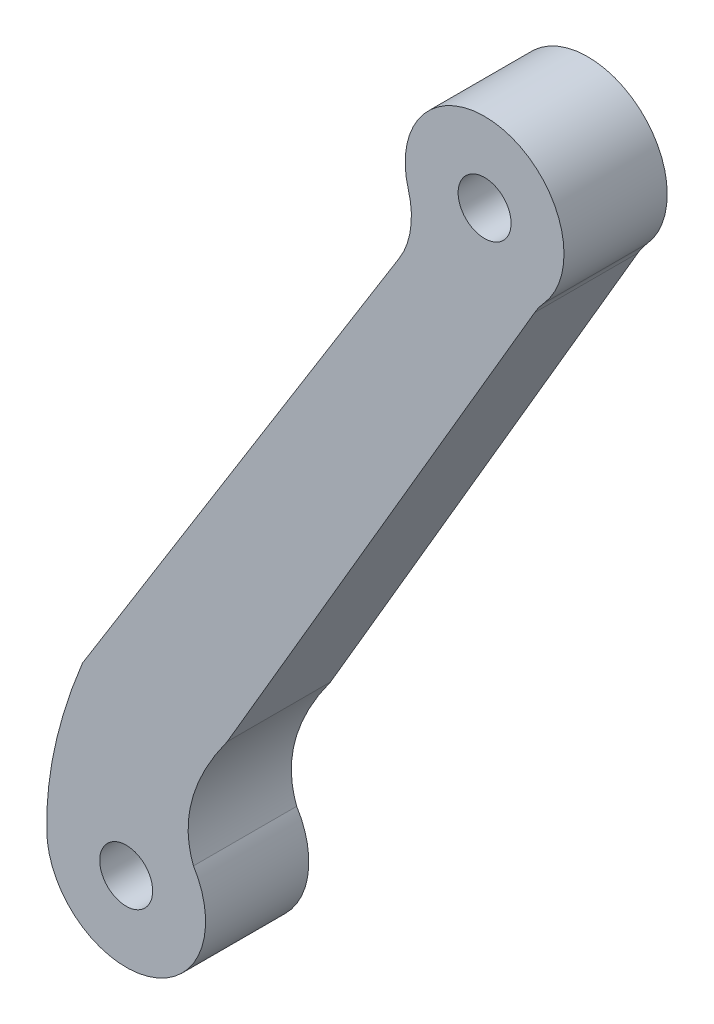
SolidWorks part; units mm, degrees
ref_plane "Спереди" through (0, 0, 0) normal (0, 0, 1) x (1, 0, 0)
ref_plane "Сверху" through (0, 0, 0) normal (0, 1, 0) x (1, 0, 0)
ref_plane "Справа" through (0, 0, 0) normal (1, 0, 0) x (0, 0, -1)
sketch "Sketch5" plane through (0, 0, 0) normal (0, 0, 1) x (1, 0, 0)
  line L0 (1.7523, 0.4742) -> (37.3029, 86.8114) construction
  line L1 (-1.0106, -0.6044) -> (29.6618, 87.5839) construction
  line L2 (0, 0) -> (17.8901, 43.1295)
  line L3 (0, 0) -> (114.3643, 0) construction
  line L4 (23.8823, 39.6684) -> (24.5035, 51.2503)
  line B0 (17.4507, 115.16) -> (29.9551, 112.6983)
  spline B1 degree 3 poles (29.9551, 112.6983) (28.321, 116.0983) (27.9284, 121.1676) (30.1713, 134.4746) (29.8473, 132.0116) (30.6222, 139.9349) (27.0176, 140.9027) knots 0 0 0 0 0.297085 0.369784 0.687298 1 1 1 1
  spline B2 degree 2 poles (27.0176, 140.9027) (20.5603, 128.6427) (17.4507, 115.16) knots 0 0 0 1 1 1
  spline B3 degree 2 poles (27.0176, 140.9027) (26.5004, 134.6878) (22.2537, 130.5645) knots 0 0 0 1 1 1
  line B4 (17.1977, 114.3508) -> (29.842, 112.2111)
  line B5 (28.7001, 84.8969) -> (10.3668, 87.513)
  spline B6 degree 1 poles (17.1977, 114.3508) (10.3668, 87.513) knots 0 0 1 1
  spline B7 degree 2 poles (29.842, 112.2111) (22.5534, 98.8452) (28.7001, 84.8969) knots 0 0 0 1 1 1
  line B8 (10.1904, 87.4159) -> (28.2572, 84.4958)
  line B9 (32.8909, 45.7292) -> (10.0695, 42.8593)
  spline B10 degree 2 poles (10.1904, 87.4159) (10.0234, 65.1379) (10.0695, 42.8593) knots 0 0 0 1 1 1
  spline B11 degree 2 poles (28.2572, 84.4958) (20.6417, 64.1094) (32.8909, 45.7292) knots 0 0 0 1 1 1
  line B12 (10.2797, 36.8758) -> (3.9253, -13.9853)
  line B13 (3.9253, -13.9853) -> (33.9594, -31.0804)
  line B14 (33.9594, -31.0804) -> (45.9193, -27.7969)
  line B15 (45.9193, -27.7969) -> (58.2918, -13.9853)
  line B16 (58.2918, -13.9853) -> (69.0331, -4.9875)
  line B17 (69.0331, -4.9875) -> (82.514, 2.0236)
  line B18 (82.514, 2.0236) -> (89.2736, 3.8794)
  line B19 (89.2736, 3.8794) -> (92.4846, 9.5208)
  line B20 (92.4846, 9.5208) -> (96.8914, 17.263)
  line B21 (96.8914, 17.263) -> (101.4978, 21.1217)
  line B22 (101.4978, 21.1217) -> (103.9241, 23.1541)
  line B23 (104.261, 27.4157) -> (104.5375, 25.5318)
  line B24 (84.192, 21.2056) -> (87.7484, 22.7822)
  line B25 (87.7484, 22.7822) -> (92.912, 27.4956)
  line B26 (71.6086, 15.6268) -> (84.192, 21.2056)
  line B27 (92.912, 27.4956) -> (95.357, 29.7274)
  line B28 (95.357, 29.7274) -> (96.8049, 29.9399)
  line B29 (71.6086, 15.6268) -> (53.4239, 15.2713)
  line B30 (48.0904, 17.5622) -> (39.9394, 26.4919)
  line B31 (39.9394, 26.4919) -> (33.9594, 37.99)
  line B32 (33.9594, 37.99) -> (10.2797, 36.8758)
  line B33 (96.8049, 29.9399) -> (99.4078, 30.2175)
  line B34 (99.4078, 30.2175) -> (102.2786, 29.261)
  line B35 (102.2786, 29.261) -> (104.261, 27.4157)
  line B36 (104.5375, 25.5318) -> (103.9241, 23.1541)
  arc B37 (53.4239, 15.2713) -> (48.0904, 17.5622) centre (53.2864, 22.3051) cw
  spline B38 degree 3 poles (104.261, 27.4157) (103.5289, 27.0494) (99.8378, 26.2685) (94.8982, 17.2338) (98.6516, 18.7375) knots 0 0 0 0 0.441207 1 1 1 1
  line B39 (27.7375, 116.5129) -> (14.1959, 87.8955)
  line B40 (27.7375, 116.5129) -> (25.9485, 114.8372)
  line B41 (25.9485, 114.8372) -> (27.5763, 114.067)
  line B42 (27.7375, 116.5129) -> (27.5763, 114.067)
  line B43 (26.1527, 88.0864) -> (17.8901, 43.1295)
  line B44 (19.3622, 85.005) -> (23.8823, 39.6684)
  line B45 (19.3622, 85.005) -> (17.7584, 73.9508)
  line B46 (17.7584, 73.9508) -> (23.117, 74.485)
  line B47 (23.117, 74.485) -> (19.3622, 85.005)
  line B48 (26.1527, 88.0864) -> (23.7481, 82.7635)
  line B49 (23.7481, 82.7635) -> (25.1278, 82.5099)
  line B50 (25.1278, 82.5099) -> (26.5087, 82.2561)
  line B51 (26.5087, 82.2561) -> (26.1527, 88.0864)
  line B52 (26.1527, 88.0864) -> (19.3622, 85.005)
  line B53 (19.3622, 85.005) -> (22.3683, 87.7853)
  line B54 (22.3683, 87.7853) -> (22.9012, 86.6109)
  line B55 (22.9012, 86.6109) -> (23.4998, 85.2917)
  line B56 (23.4998, 85.2917) -> (19.3622, 85.005)
  dimension "D1" = 93.37
  dimension "D2" = 93.37
  dimension "D4" = 67.471
  dimension "D5" = 8.764
sketch_block_instance "Block1-1"
sketch_block "Block1"
sketch_block_instance "Block2-1"
sketch_block "Block2"
sketch_block_instance "Block3-1"
sketch_block "Block3"
sketch_block_instance "Block18-1"
sketch_block "Block18"
sketch_block_instance "Block44-1"
sketch_block "Block44"
sketch_block_instance "Block46-1"
sketch_block "Block46"
sketch_block_instance "Block47-1"
sketch_block "Block47"
sketch_block_instance "Block48-1"
sketch_block "Block48"
sketch_block_instance "Block50-1"
sketch_block "Block50"
sketch "Sketch6" plane through (0, 0, 0) normal (0, 0, 1) x (1, 0, 0)
  line L0 (12.546, 94.0292) -> (24.519, 113.2669)
  line L5 (29.6287, 114.0374) -> (18.0165, 94.1948)
  line L6 (12.546, 94.0292) -> (11.1432, 90.6208) construction
  line L7 (11.1432, 90.6208) -> (11.1959, 87.8955) construction
  line L8 (18.0165, 94.1948) -> (15.9886, 91.4158) construction
  line L9 (15.9886, 91.4158) -> (16.739, 89.4869) construction
  arc A0 (29.9777, 114.5175) -> (29.6287, 114.0374) centre (32.218, 112.5222) ccw
  circle A1 centre (14.1959, 87.8955) radius 3
  circle A2 centre (27.7375, 116.5129) radius 1
  circle A3 centre (14.1959, 87.8955) radius 1
  arc A4 (29.9777, 114.5175) -> (24.8547, 115.6825) centre (27.7375, 116.5129) ccw
  arc A5 (24.519, 113.2669) -> (24.8547, 115.6825) centre (21.972, 114.8521) ccw
  spline S2 degree 2 poles (12.546, 94.0292) (11.1432, 90.6208) (11.1959, 87.8955) knots 0 0 0 1 1 1
  spline S3 degree 2 poles (18.0165, 94.1948) (15.9886, 91.4158) (16.739, 89.4869) knots 0 0 0 1 1 1
  dimension "D1" = 2
  dimension "D2" = 6
  dimension "D3" = 3
extrude "Boss-Extrude1" add sketch "Sketch6" along normal blind 3.9
